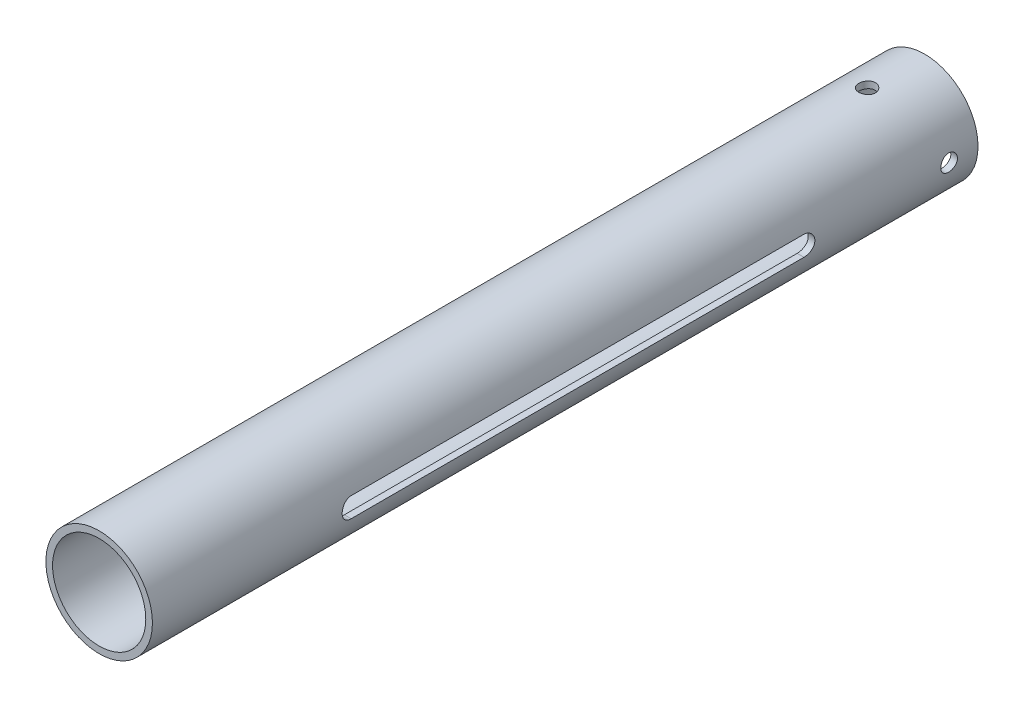
SolidWorks part; units mm, degrees
material "AISI 1010 Steel, hot rolled bar"
ref_plane "Front Plane" through (0, 0, 0) normal (0, 0, 1) x (1, 0, 0)
ref_plane "Top Plane" through (0, 0, 0) normal (0, 1, 0) x (1, 0, 0)
ref_plane "Right Plane" through (0, 0, 0) normal (1, 0, 0) x (0, 0, -1)
sketch "Sketch1" plane through (0, 0, 0) normal (0, 0, 1) x (1, 0, 0)
  line L0 (-25.4, 0) -> (-22.225, 0) construction
  circle A0 centre (0, 0) radius 22.225 construction
  circle A1 centre (0, 0) radius 25.4 construction
  dimension "OD" = 50.8
  dimension "ID" = 44.45
  dimension "Wall Thickness" = 3.175
sketch "Sketch2" plane through (0, 0, 0) normal (1, 0, 0) x (0, 0, -1)
  line L0 (-152.4, -25.4) -> (152.4, -25.4) construction
  point P2 (0, -25.4)
  point P3 (76.2, -25.4)
  point P4 (-76.2, -25.4)
  dimension "Length" = 304.8
  dimension "D1" = 76.2
  dimension "D2" = 76.2
sketch "Sketch3" plane through (0, 0, 0) normal (0, 0, 1) x (1, 0, 0)
  circle A0 centre (0, 0) radius 22.225 construction
  circle A1 centre (0, 0) radius 25.4 construction
  circle A2 centre (0, 0) radius 22.225
  circle A3 centre (0, 0) radius 25.4
extrude "Boss-Extrude2" add sketch "Sketch3" along normal up to vertex (152.4 mm away) and the other way up to vertex (152.4 mm away) up to point (0, -25.4, 152.4) other way up to point (0, -25.4, -152.4)
sketch "Sketch4" plane through (0, 0, 152.4) normal (0, 0, 1) x (1, 0, 0)
  circle A0 centre (0, 0) radius 36.4857
extrude "Cut-Extrude1" [suppressed] cut sketch "Sketch4" against normal offset from surface (12.7 mm away) 12.7
sketch "Sketch9" plane through (0, 0, 152.4) normal (0, 0, 1) x (1, 0, 0)
  circle A0 centre (0, 0) radius 22.225
  circle A1 centre (0, 0) radius 25.4
extrude "Boss-Extrude3" add sketch "Sketch9" along normal blind 88.9
sketch "Sketch5" plane through (0, 0, 0) normal (1, 0, 0) x (0, 0, -1)
  line L0 (-38.1, 0) -> (69.85, 0) construction
  line L1 (-38.1, 0) -> (-146.05, 0) construction
  line L2 (-241.3, 0) -> (152.4, 0) construction
  line L3 (152.4, -25.4) -> (152.4, 25.4) construction
  line L5 (-146.05, 4.7625) -> (69.85, 4.7625)
  line L6 (69.85, -4.7625) -> (-146.05, -4.7625)
  line L7 (-38.1, 4.7625) -> (-38.1, -4.7625) construction
  line L8 (-241.3, 25.4) -> (-241.3, -25.4) construction
  circle A0 centre (-146.05, 0) radius 4.7625 construction
  arc A2 (-146.05, 4.7625) -> (-146.05, -4.7625) centre (-146.05, 0) ccw
  circle A4 centre (69.85, 0) radius 4.7625 construction
  arc A5 (69.85, 4.7625) -> (69.85, -4.7625) centre (69.85, 0) cw
  point P13 (-38.1, 4.7625)
  point P14 (-38.1, -4.7625)
  point P17 (-38.1, 0)
  dimension "D1" = 107.95
  dimension "D2" = 82.55
  dimension "D3" = 9.525
extrude "Cut-Extrude2" cut sketch "Sketch5" against normal through all both and the other way through all
sketch "Sketch6" plane through (0, 0, 0) normal (1, 0, 0) x (0, 0, -1)
  line L0 (152.4, -25.4) -> (152.4, 25.4) construction
  line L1 (111.125, 0) -> (124.8833, 0) construction
  line L2 (124.8833, 0) -> (138.6417, 0) construction
  line L3 (138.6417, 0) -> (152.4, 0) construction
  circle A0 centre (138.6417, 0) radius 3.9687
  point P0 (111.125, 0)
  point P1 (124.8833, 0)
  point P2 (138.6417, 0)
  point P3 (152.4, 0)
  dimension "D2" = 7.9375
  dimension "D1" = 41.275
extrude "Cut-Extrude3" cut sketch "Sketch6" against normal through all both and the other way through all
sketch "Sketch8" plane through (0, 0, 0) normal (0, 1, 0) x (1, 0, 0)
  line L1 (0, 111.125) -> (0, 124.8833) construction
  line L2 (0, 124.8833) -> (0, 138.6417) construction
  line L3 (0, 138.6417) -> (0, 152.4) construction
  line L4 (25.4, 152.4) -> (-25.4, 152.4) construction
  circle A1 centre (0, 124.8833) radius 3.9688
  point P0 (0, 111.125)
  point P1 (0, 124.8833)
  point P2 (0, 138.6417)
  point P3 (0, 152.4)
  dimension "D2" = 7.9375
  dimension "D1" = 41.275
extrude "Cut-Extrude4" cut sketch "Sketch8" against normal through all both and the other way through all
equation "\"D1@Sketch2\"=\"OD@Sketch1\"*1.5"
equation "\"D2@Sketch2\"=\"D1@Sketch2\""
